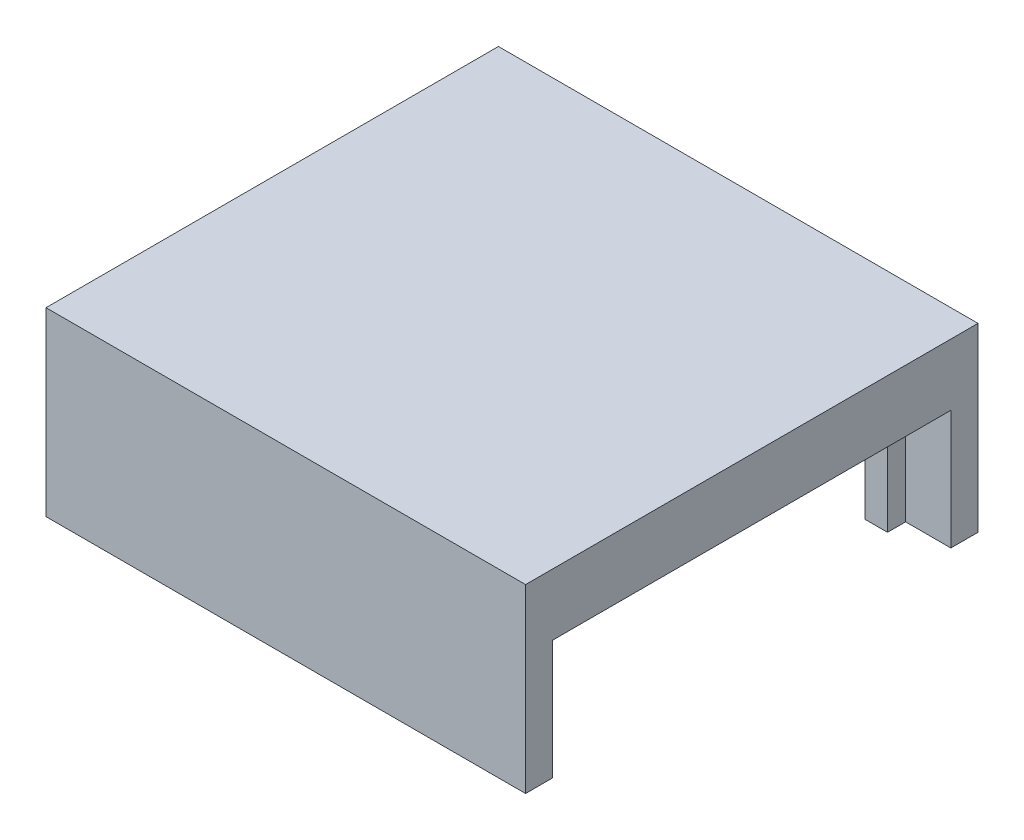
SolidWorks part; units mm, degrees
ref_plane "Front Plane" through (0, 0, 0) normal (0, 0, 1) x (1, 0, 0)
ref_plane "Top Plane" through (0, 0, 0) normal (0, 1, 0) x (1, 0, 0)
ref_plane "Right Plane" through (0, 0, 0) normal (1, 0, 0) x (0, 0, -1)
sketch "Sketch1" plane through (0, 0, 0) normal (0, 1, 0) x (1, 0, 0)
  line L1 (53, -50) -> (-53, -50)
  line L2 (53, -50) -> (53, 50)
  line L3 (53, 50) -> (-53, 50)
  line L4 (-53, -50) -> (-53, 50)
  line L5 (53, -50) -> (-53, 50) construction
  line L6 (53, 50) -> (-53, -50) construction
  point P0 (0, 0)
  dimension "D1" = 100
  dimension "D2" = 106
extrude "Boss-Extrude1" add sketch "Sketch1" along normal blind 40
sketch "Sketch2" plane through (0, 0, 0) normal (0, -1, 0) x (1, 0, 0)
  line L0 (-53, 50) -> (53, 50) construction
  line L1 (-43, 40) -> (43, 40)
  line L2 (-43, 40) -> (-43, -40)
  line L3 (-43, -40) -> (43, -40)
  line L4 (43, 40) -> (43, -40)
  line L5 (53, -50) -> (-53, -50) construction
  line L6 (53, 50) -> (53, -50) construction
  line L7 (-53, -50) -> (-53, 50) construction
  point P0 (0, 4.8884)
  dimension "D1" = 10
  dimension "D2" = 10
  dimension "D3" = 10
  dimension "D4" = 10
extrude "Cut-Extrude1" cut sketch "Sketch2" against normal offset from surface (35 mm away) 5 up to face at (0, 40, 0)
sketch "Sketch3" plane through (53, 0, 0) normal (1, 0, 0) x (0, 0, -1)
  line L0 (-50, 0) -> (50, 0) construction
  line L1 (-44, 0) -> (44, 0)
  line L2 (-44, 0) -> (-44, 26.3579)
  line L3 (-44, 26.3579) -> (44, 26.3579)
  line L4 (44, 0) -> (44, 26.3579)
  line L5 (-50, 40) -> (-50, 0) construction
  line L6 (50, 40) -> (50, 0) construction
  dimension "D1" = 6
  dimension "D2" = 6
extrude "Cut-Extrude2" cut sketch "Sketch3" against normal up to surface (10 mm away) and the other way through all up to face at (43, 17.5, 0)
sketch "Sketch4" plane through (-53, 0, 0) normal (-1, 0, 0) x (0, 0, 1)
  line L0 (-50, 0) -> (50, 0) construction
  line L1 (-45, 0) -> (45, 0)
  line L2 (-45, 0) -> (-45, 33.5976)
  line L3 (-45, 33.5976) -> (45, 33.5976)
  line L4 (45, 0) -> (45, 33.5976)
  line L5 (-50, 40) -> (-50, 0) construction
  line L6 (50, 40) -> (50, 0) construction
  dimension "D1" = 5
  dimension "D2" = 5
extrude "Cut-Extrude3" cut sketch "Sketch4" against normal up to surface (10 mm away) up to face at (-43, 17.5, 0)
sketch "Sketch5" plane through (0, 0, -50) normal (0, 0, -1) x (-1, 0, 0)
  line L0 (-53, 0) -> (53, 0) construction
  line L1 (53, 40) -> (53, 0) construction
  line L2 (38, 0) -> (-38, 0)
  line L3 (38, 0) -> (38, 20.5087)
  line L4 (38, 20.5087) -> (-38, 20.5087)
  line L5 (-38, 0) -> (-38, 20.5087)
  line L6 (-53, 40) -> (-53, 0) construction
  dimension "D1" = 15
  dimension "D2" = 15
extrude "Cut-Extrude4" cut sketch "Sketch5" against normal up to surface (10 mm away) up to face at (0, 21.6593, -40)
